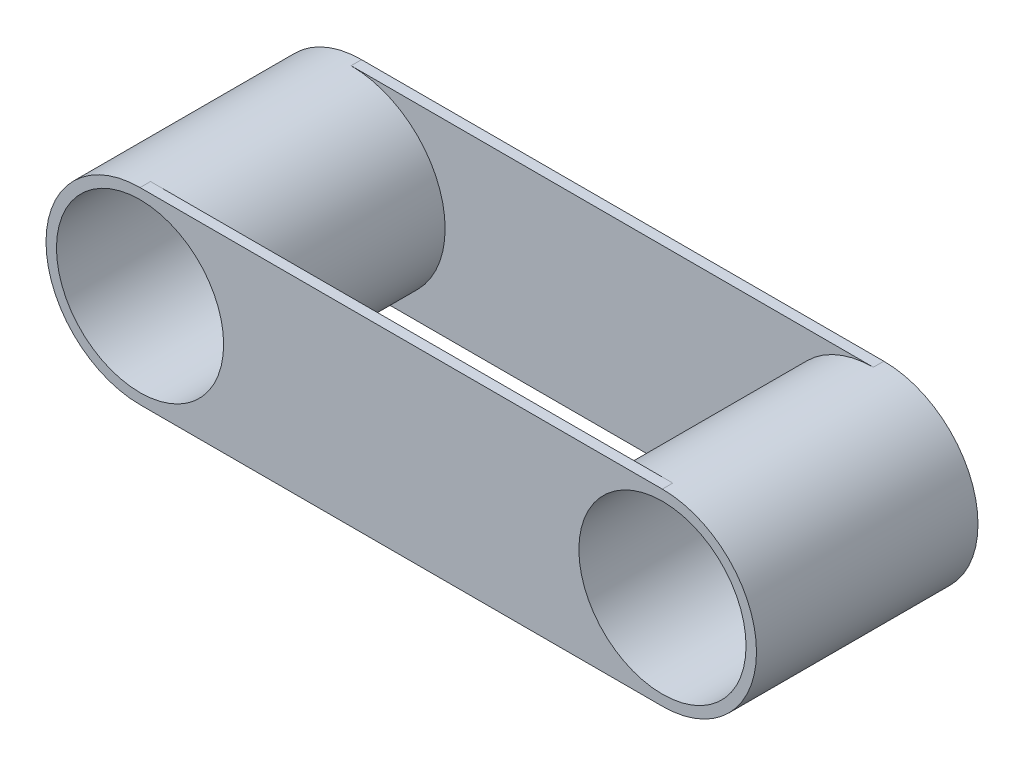
SolidWorks part; units mm, degrees
material "6061-T6 (SS)"
ref_plane "Front Plane" through (0, 0, 0) normal (0, 0, 1) x (1, 0, 0)
ref_plane "Top Plane" through (0, 0, 0) normal (0, 1, 0) x (1, 0, 0)
ref_plane "Right Plane" through (0, 0, 0) normal (1, 0, 0) x (0, 0, -1)
sketch "Sketch1" plane through (0, 0, 0) normal (0, 0, 1) x (1, 0, 0)
  circle A0 centre (0, 0) radius 90
  circle A1 centre (0, 0) radius 80
  dimension "D1" = 180
  dimension "D2" = 10
extrude "Boss-Extrude1" add sketch "Sketch1" along normal mid plane 212
sketch "Sketch2" plane through (0, 0, 106) normal (0, 0, 1) x (1, 0, 0)
  line L0 (0, 0) -> (499.88, 0) construction
  line L1 (0, 90) -> (499.88, 90)
  line L2 (499.88, 90) -> (499.88, -90)
  line L3 (499.88, -90) -> (0, -90)
  circle A0 centre (0, 0) radius 90 construction
  arc A1 (0, -90) -> (0, 90) centre (0, 0) ccw
  dimension "D1" = 499.88
extrude "Boss-Extrude2" add sketch "Sketch2" against normal blind 10 contours L1 L2 L3 A1
ref_plane "Plane1" through (0, 0, 0) normal (0, 0, 1) x (1, 0, 0)
mirror "Mirror1" about plane through (0, 0, 0) normal (0, 0, 1) of "Boss-Extrude2"
ref_plane "Plane2" through (500, 0, 0) normal (1, 0, 0) x (0, 0, -1)
ref_plane "Plane3" through (250, 0, 0) normal (1, 0, 0) x (0, 0, -1)
mirror "Mirror2" about plane through (250, 0, 0) normal (1, 0, 0) of "Boss-Extrude1"
sketch "Sketch3" plane through (0, 0, -96) normal (0, 0, 1) x (1, 0, 0)
  line L1 (499.88, -79.9999) -> (499.88, 79.9999)
  line L2 (499.88, -79.9999) -> (499.88, 79.9999)
  arc A1 (499.88, 79.9999) -> (499.88, -79.9999) centre (500, 0) ccw
  arc A2 (499.88, 79.9999) -> (499.88, -79.9999) centre (500, 0) ccw
  dimension "D1" = 0
extrude "Cut-Extrude1" cut sketch "Sketch3" against normal through all both and the other way through all
